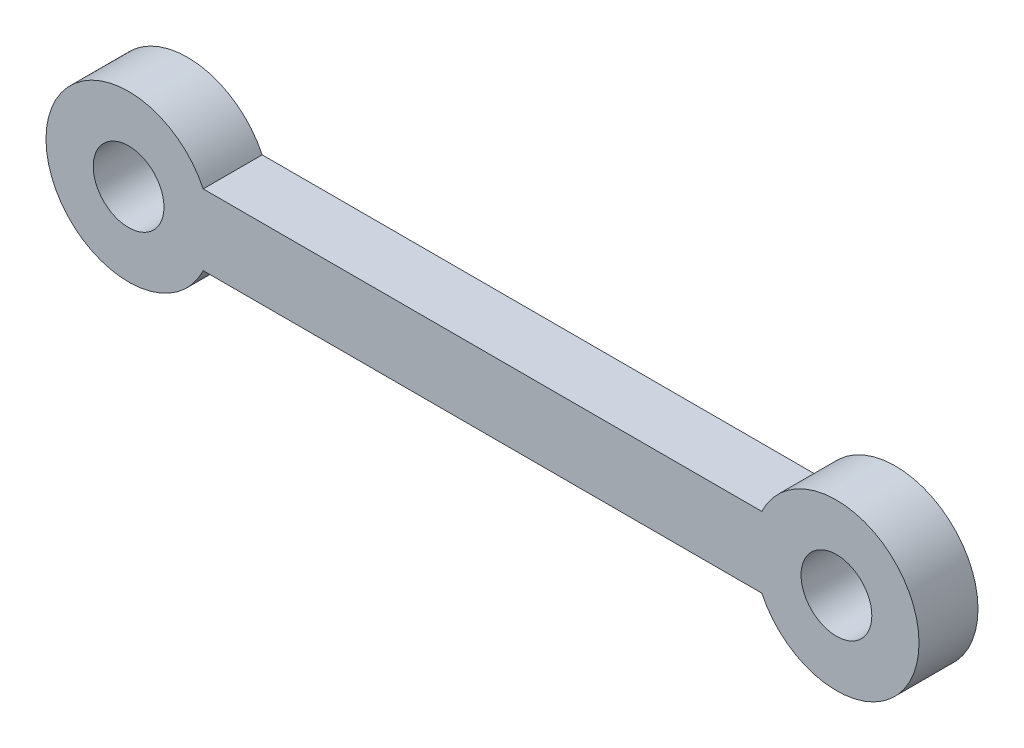
SolidWorks part; units mm, degrees
material "Cast Stainless Steel"
ref_plane "Front Plane" through (0, 0, 0) normal (0, 0, 1) x (1, 0, 0)
ref_plane "Top Plane" through (0, 0, 0) normal (0, 1, 0) x (1, 0, 0)
ref_plane "Right Plane" through (0, 0, 0) normal (1, 0, 0) x (0, 0, -1)
sketch "Sketch1" plane through (0, 0, 0) normal (0, 0, 1) x (1, 0, 0)
  line L0 (-15, 0) -> (11.5, 0) construction
  line L1 (-12.5, 0) -> (-12.5, -1.5) construction
  line L2 (-11.8377, 1.5) -> (11.8377, 1.5)
  line L3 (-12.5, 1.5) -> (-12.5, 0) construction
  line L4 (-11.8377, -1.5) -> (11.8377, -1.5)
  line L5 (12.5, 1.5) -> (12.5, 0) construction
  line L6 (-11.7992, 1.4159) -> (11.7992, -1.4159) construction
  line L7 (-11.7992, -1.4159) -> (11.7992, 1.4159) construction
  line L8 (-12.5, 1.5) -> (-11.7992, 1.4159) construction
  line L9 (-12.5, 1.5) -> (-11.8377, 1.5) construction
  line L10 (-12.5, -1.5) -> (-11.7992, -1.4159) construction
  line L11 (-12.5, -1.5) -> (-11.8377, -1.5) construction
  line L12 (11.7992, -1.4159) -> (12.5, -1.5) construction
  line L13 (11.8377, -1.5) -> (12.5, -1.5) construction
  line L14 (12.5, 0) -> (12.5, -1.5) construction
  line L15 (11.5, 0) -> (12.5, 0) construction
  line L16 (12.5, 0) -> (15, 0) construction
  line L17 (11.7992, 1.4159) -> (12.5, 1.5) construction
  line L18 (11.8377, 1.5) -> (12.5, 1.5) construction
  circle A0 centre (-15, 0) radius 1.5
  circle A1 centre (15, 0) radius 1.5
  arc A2 (-11.8377, 1.5) -> (-11.8377, -1.5) centre (-15, 0) ccw
  arc A3 (11.8377, -1.5) -> (11.8377, 1.5) centre (15, 0) ccw
  arc A4 (-11.5, 0) -> (-11.7992, 1.4159) centre (-15, 0) ccw construction
  arc A5 (-11.7992, -1.4159) -> (-11.5, 0) centre (-15, 0) ccw construction
  arc A6 (-11.8377, -1.5) -> (-11.7992, -1.4159) centre (-15, 0) ccw construction
  arc A7 (11.5, 0) -> (11.7992, -1.4159) centre (15, 0) ccw construction
  arc A8 (11.7992, 1.4159) -> (11.5, 0) centre (15, 0) ccw construction
  arc A9 (11.8377, 1.5) -> (11.7992, 1.4159) centre (15, 0) ccw construction
  arc A10 (11.7992, -1.4159) -> (11.8377, -1.5) centre (15, 0) ccw construction
  arc A11 (-11.7992, 1.4159) -> (-11.8377, 1.5) centre (-15, 0) ccw construction
  point P4 (0, 0)
  point P9 (0, 0)
  dimension "D2" = 3
  dimension "D3" = 7
  dimension "D1" = 30
  dimension "D4" = 3
  dimension "D5" = 25
extrude "Boss-Extrude1" add sketch "Sketch1" along normal blind 2.5
